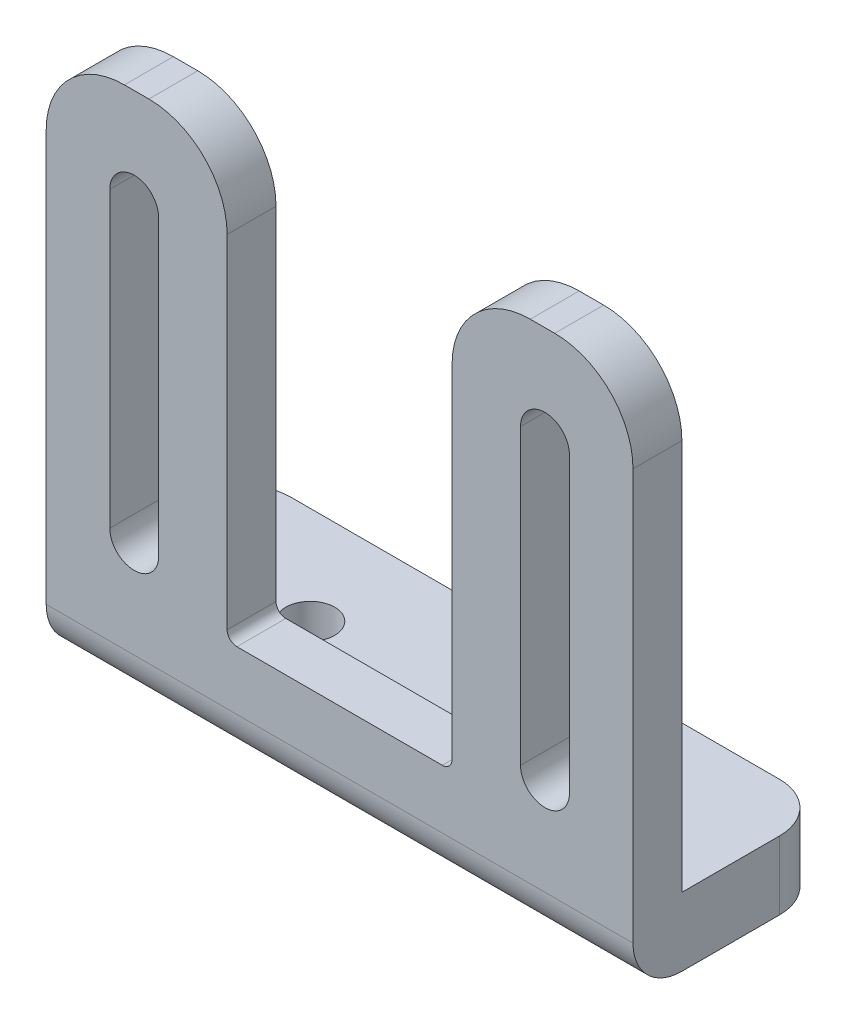
SolidWorks part; units mm, degrees
ref_plane "Front Plane" through (0, 0, 0) normal (0, 0, 1) x (1, 0, 0)
ref_plane "Top Plane" through (0, 0, 0) normal (0, 1, 0) x (1, 0, 0)
ref_plane "Right Plane" through (0, 0, 0) normal (1, 0, 0) x (0, 0, -1)
sketch "Sketch1" plane through (0, 0, 0) normal (0, 0, 1) x (1, 0, 0)
  line L1 (0, 0) -> (60, 0)
  line L2 (0, 0) -> (0, 55)
  line L3 (0, 55) -> (60, 55)
  line L4 (60, 0) -> (60, 55)
  dimension "D1" = 55
  dimension "D2" = 60
extrude "Boss-Extrude1" add sketch "Sketch1" along normal blind 5
sketch "Sketch2" plane through (0, 0, 5) normal (0, 0, 1) x (1, 0, 0)
  line L0 (9, 45) -> (9, 15) construction
  line L1 (11.5, 45) -> (11.5, 15)
  line L2 (6.5, 45) -> (6.5, 15)
  line L3 (51, 45) -> (51, 15) construction
  line L4 (53.5, 45) -> (53.5, 15)
  line L5 (48.5, 45) -> (48.5, 15)
  line L6 (9, 45) -> (0, 55) construction
  line L7 (51, 45) -> (60, 55) construction
  line L8 (0, 0) -> (60, 0) construction
  line L9 (60, 55) -> (0, 55) construction
  line L12 (18.5, 55) -> (41.5, 55)
  line L14 (18.5, 55) -> (18.5, 11)
  line L15 (18.5, 11) -> (41.5, 11)
  line L16 (41.5, 55) -> (41.5, 11)
  line L17 (30, -945) -> (30, 49055) construction
  arc A0 (11.5, 45) -> (6.5, 45) centre (9, 45) ccw
  arc A1 (6.5, 15) -> (11.5, 15) centre (9, 15) ccw
  arc A2 (53.5, 45) -> (48.5, 45) centre (51, 45) ccw
  arc A3 (48.5, 15) -> (53.5, 15) centre (51, 15) ccw
  point P2 (9, 30)
  point P7 (51, 30)
  point P31 (30, 55)
  dimension "D2" = 2.5
  dimension "D1" = 42
  dimension "D3" = 30
  dimension "D4" = 15
  dimension "D6" = 7
  dimension "D5" = 7
  dimension "D7" = 4
extrude "Cut-Extrude1" cut sketch "Sketch2" against normal up to next
sketch "Sketch3" plane through (0, 0, 0) normal (0, 0, -1) x (-1, 0, 0)
  line L0 (-60, 0) -> (-60, 55) construction
  line L1 (0, 0) -> (-60, 0)
  line L2 (0, 0) -> (0, 7)
  line L3 (0, 7) -> (-60, 7)
  line L4 (-60, 0) -> (-60, 7)
  dimension "D1" = 7
extrude "Boss-Extrude2" add sketch "Sketch3" along normal blind 15
sketch "Sketch4" plane through (0, 7, 0) normal (0, 1, 0) x (1, 0, 0)
  line L0 (0, 15) -> (60, 15) construction
  line L1 (17, 5) -> (0, 15) construction
  line L2 (43, 5) -> (60, 15) construction
  circle A0 centre (17, 5) radius 2.5
  circle A1 centre (43, 5) radius 2.5
  dimension "D1" = 5
  dimension "D2" = 10
  dimension "D3" = 26
extrude "Cut-Extrude2" cut sketch "Sketch4" against normal up to next
fillet "Fillet1" radius 8 4 edges at (0, 55, 2.5) (60, 55, 2.5) (41.5, 55, 2.5) (18.5, 55, 2.5)
fillet "Fillet2" radius 5 2 edges at (60, 3.5, -15) (0, 3.5, -15)
fillet "Fillet3" radius 5 1 edges at (30, 0, 5)
fillet "Fillet4" radius 1 2 edges at (18.5, 11, 2.5) (41.5, 11, 2.5)
